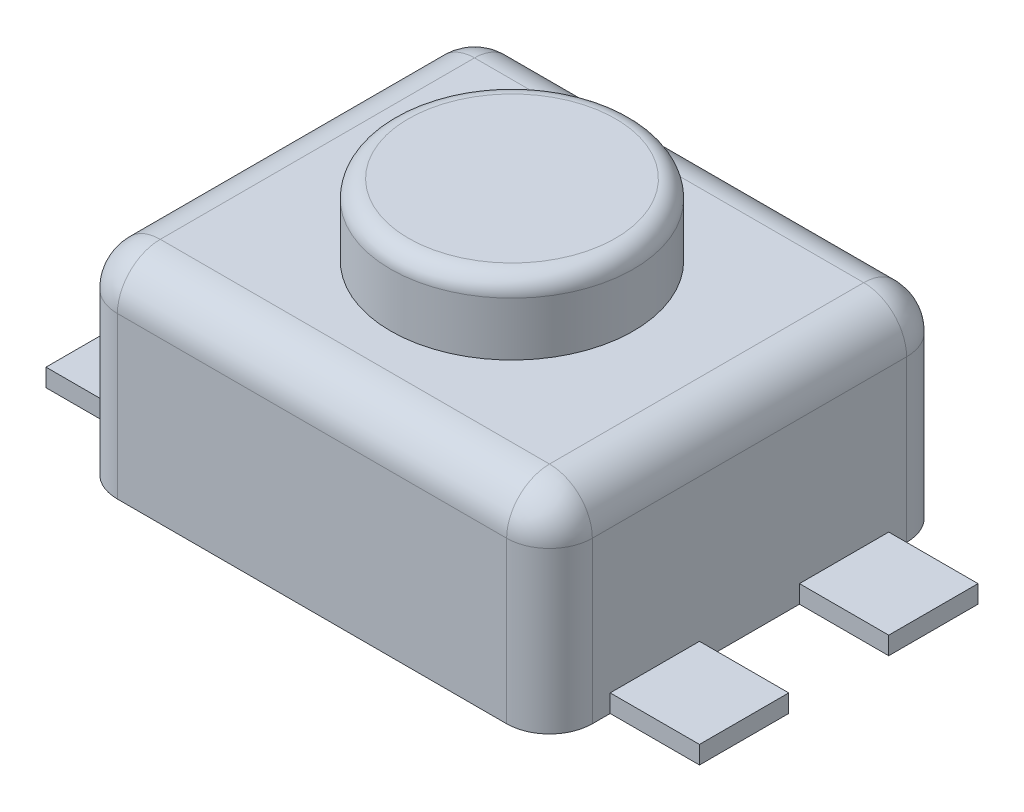
SolidWorks part; units mm, degrees
ref_plane "Front Plane" through (0, 0, 0) normal (0, 0, 1) x (1, 0, 0)
ref_plane "Top Plane" through (0, 0, 0) normal (0, 1, 0) x (1, 0, 0)
ref_plane "Right Plane" through (0, 0, 0) normal (1, 0, 0) x (0, 0, -1)
sketch "Sketch1" plane through (0, 0, 0) normal (0, 1, 0) x (1, 0, 0)
  line L1 (-1.6891, 1.4224) -> (1.6891, 1.4224)
  line L2 (-1.6891, 1.4224) -> (-1.6891, -1.4224)
  line L3 (-1.6891, -1.4224) -> (1.6891, -1.4224)
  line L4 (1.6891, 1.4224) -> (1.6891, -1.4224)
  line L5 (-1.6891, 1.4224) -> (1.6891, -1.4224) construction
  line L6 (-1.6891, -1.4224) -> (1.6891, 1.4224) construction
  point P0 (0, 0)
  dimension "D1" = 3.3782
  dimension "D2" = 2.8448
extrude "Boss-Extrude1" add sketch "Sketch1" along normal blind 1.4478
fillet "Fillet1" radius 0.3048 8 edges at (0, 1.4478, 1.4224) (-1.6891, 1.4478, 0) (0, 1.4478, -1.4224) (1.6891, 1.4478, 0) (-1.6891, 0.7239, 1.4224) (-1.6891, 0.7239, -1.4224) (1.6891, 0.7239, -1.4224) (1.6891, 0.7239, 1.4224)
sketch "Sketch2" plane through (0, 1.4478, 0) normal (0, 1, 0) x (1, 0, 0)
  circle A0 centre (0, 0) radius 0.8636
  dimension "D1" = 1.7272
extrude "Boss-Extrude2" add sketch "Sketch2" along normal blind 0.508
fillet "Fillet2" radius 0.127 1 edges at (0, 1.9558, 0.8636)
sketch "Sketch3" plane through (0, 0, 0) normal (0, 1, 0) x (1, 0, 0)
  line L0 (-1.6891, 1.1176) -> (-1.6891, -1.1176) construction
  line L1 (-1.6891, 0.3556) -> (-2.3241, 0.3556)
  line L2 (-1.6891, 0.3556) -> (-1.6891, 0.9906)
  line L3 (-1.6891, 0.9906) -> (-2.3241, 0.9906)
  line L4 (-2.3241, 0.3556) -> (-2.3241, 0.9906)
  line L5 (-1.6891, -0.9906) -> (-2.3241, -0.9906)
  line L6 (-1.6891, -0.9906) -> (-1.6891, -0.3556)
  line L7 (-1.6891, -0.3556) -> (-2.3241, -0.3556)
  line L8 (-2.3241, -0.9906) -> (-2.3241, -0.3556)
  line L9 (-1.6891, -0.3556) -> (-1.6891, 0.3556) construction
  line L10 (-1.6891, -1.1176) -> (-1.6891, 1.1176) construction
  point P11 (-1.6891, 0)
  point P14 (-1.6891, 0)
  dimension "D1" = 0.635
  dimension "D2" = 0.127
extrude "Boss-Extrude3" add sketch "Sketch3" along normal blind 0.127
mirror "Mirror1" about plane through (0, 0, 0) normal (1, 0, 0) of "Boss-Extrude3"
